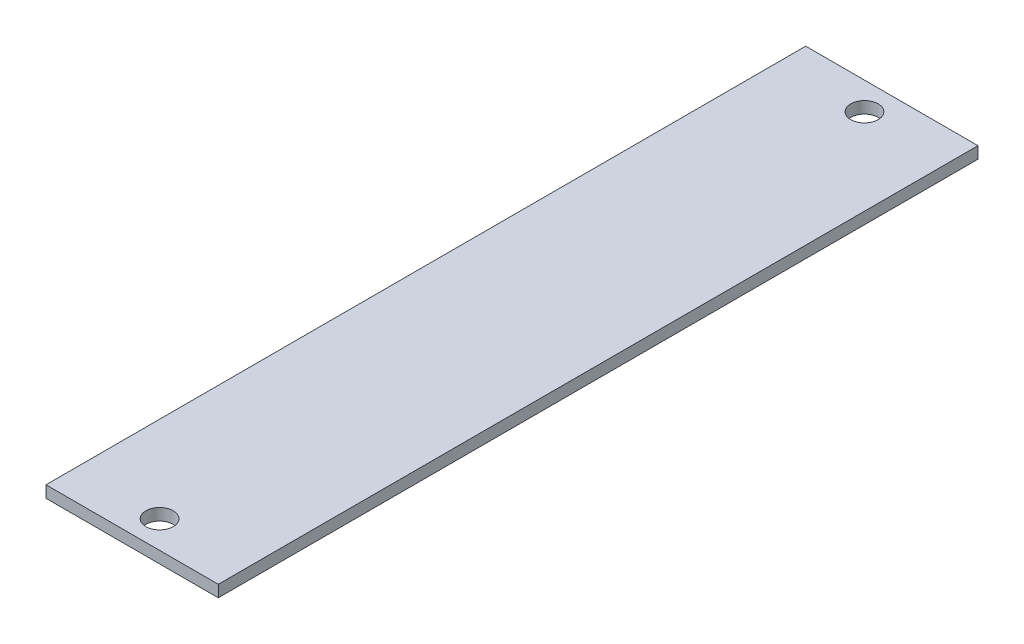
SolidWorks part; units mm, degrees
ref_plane "Front Plane" through (0, 0, 0) normal (0, 0, 1) x (1, 0, 0)
ref_plane "Top Plane" through (0, 0, 0) normal (0, 1, 0) x (1, 0, 0)
ref_plane "Right Plane" through (0, 0, 0) normal (1, 0, 0) x (0, 0, -1)
sketch "Sketch1" plane through (0, 0, 0) normal (0, 1, 0) x (1, 0, 0)
  line L1 (-11, -48.5) -> (11, -48.5)
  line L2 (-11, -48.5) -> (-11, 48.5)
  line L3 (-11, 48.5) -> (11, 48.5)
  line L4 (11, -48.5) -> (11, 48.5)
  line L5 (-11, -48.5) -> (11, 48.5) construction
  line L6 (-11, 48.5) -> (11, -48.5) construction
  point P0 (0, 0)
  dimension "D1" = 97
  dimension "D2" = 22
extrude "Boss-Extrude1" add sketch "Sketch1" along normal blind 1.5 contours L1 L4 L3 L2
sketch "Sketch2" plane through (0, 1.5, 0) normal (0, 1, 0) x (1, 0, 0)
  line L1 (-11, 48.5) -> (11, 48.5) construction
  line L2 (-11, -48.5) -> (11, -48.5) construction
  circle A0 centre (0, 45) radius 1.75
  circle A1 centre (0, -45) radius 1.75
  point P4 (0, 0)
  point P5 (0, 0)
  point P7 (0, 0)
  dimension "D1" = 3.5
  dimension "D2" = 3.5
  dimension "D3" = 3.5
extrude "Cut-Extrude1" cut sketch "Sketch2" against normal through all
equation "\"D2@Sketch2\"=1.75 + \"D1@Sketch2\"/2"
